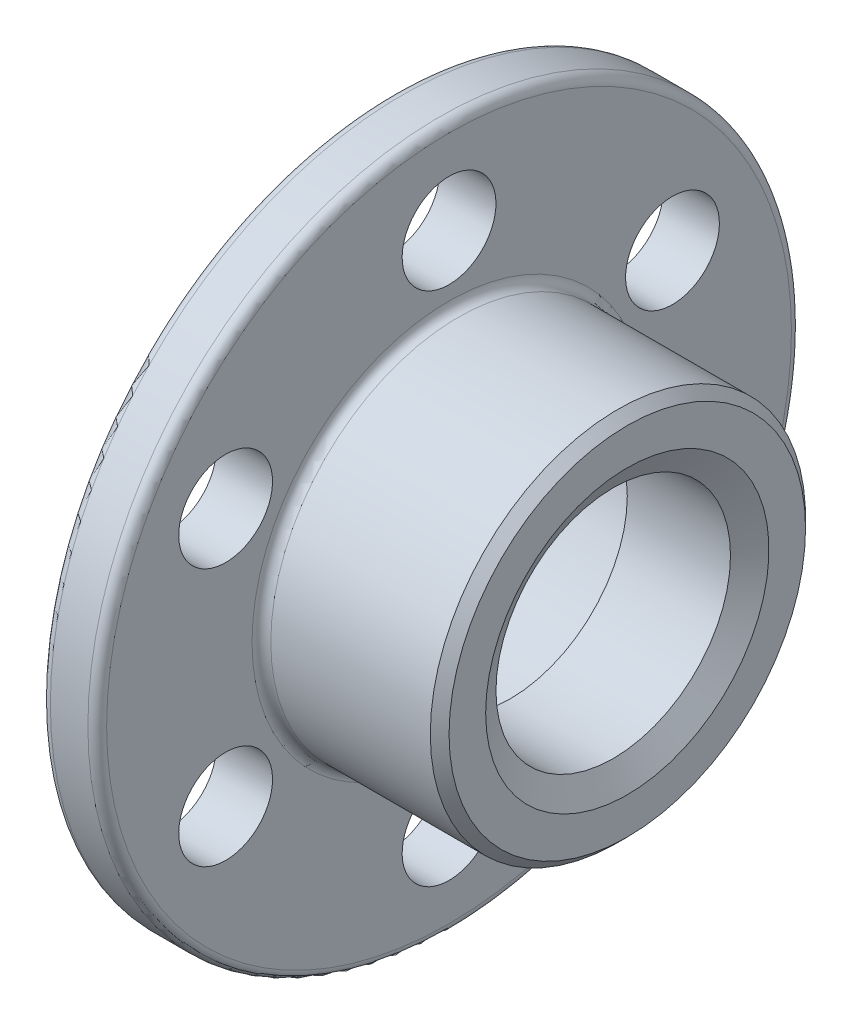
SolidWorks part; units mm, degrees
material "Латунь"
ref_plane "Спереди" through (0, 0, 0) normal (0, 0, 1) x (1, 0, 0)
ref_plane "Сверху" through (0, 0, 0) normal (0, 1, 0) x (1, 0, 0)
ref_plane "Справа" through (0, 0, 0) normal (1, 0, 0) x (0, 0, -1)
sketch "Эскиз1" plane through (0, 0, 0) normal (0, 0, 1) x (1, 0, 0)
  line L0 (0, 0) -> (36.6212, 0) construction
  line L1 (0, 35) -> (25, 35)
  line L2 (25, 35) -> (25, 25)
  line L3 (25, 25) -> (50, 25)
  line L4 (50, 25) -> (50, 40)
  line L5 (50, 40) -> (12, 40)
  line L6 (12, 40) -> (12, 75)
  line L7 (12, 75) -> (0, 75)
  line L8 (0, 75) -> (0, 35)
  dimension "D1" = 70
  dimension "D2" = 25
  dimension "D3" = 50
  dimension "D4" = 80
  dimension "D5" = 50
  dimension "D6" = 150
  dimension "D7" = 38
revolve "Повернуть1" add sketch "Эскиз1" angle 360 about L0
sketch "Эскиз2" plane through (0, 0, 0) normal (0, 0, 1) x (1, 0, 0)
  line L0 (0, 75) -> (0, -75) construction
  line L1 (0, 65) -> (12, 65)
  line L2 (0, 65) -> (0, 55)
  line L3 (0, 55) -> (12, 55)
  line L4 (12, 65) -> (12, 55)
  line L5 (12, -75) -> (12, 75) construction
  line L6 (12, 55) -> (30.3208, 55) construction
  dimension "D1" = 10
  dimension "D2" = 55
revolve "Вырез-Повернуть1" cut sketch "Эскиз2" angle 360 about L6
pattern_circular "Круговой массив1" count 6 over 360 about axis through (0, 0, 0) along (1, 0, 0) of "Вырез-Повернуть1"
fillet "Скругление1" radius 2 3 edges at (12, 0, 40) (12, 0, 75) (0, 0, 75)
chamfer "Фаска1" distance 2 angle 45 1 edges at (50, 0, 40)
chamfer "Фаска3" distance 3 angle 60 1 edges at (50, 0, 25)
